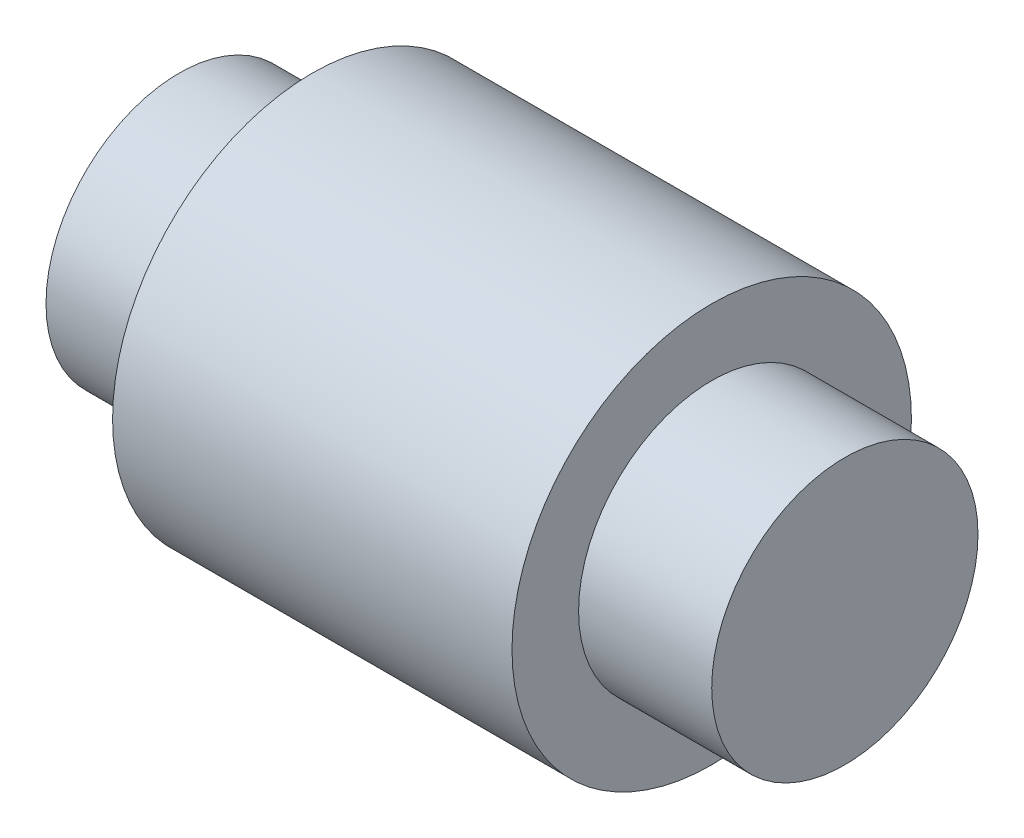
SolidWorks part; units mm, degrees
ref_plane "Спереди" through (0, 0, 0) normal (0, 0, 1) x (1, 0, 0)
ref_plane "Сверху" through (0, 0, 0) normal (0, 1, 0) x (1, 0, 0)
ref_plane "Справа" through (0, 0, 0) normal (1, 0, 0) x (0, 0, -1)
sketch "Эскиз1" plane through (0, 0, 0) normal (0, 0, 1) x (1, 0, 0)
  line L0 (0, 0) -> (100, 0)
  line L1 (0, 0) -> (0, 20)
  line L2 (0, 20) -> (20, 20)
  line L3 (20, 20) -> (20, 30)
  line L4 (20, 30) -> (80, 30)
  line L5 (80, 30) -> (80, 20)
  line L6 (80, 20) -> (100, 20)
  line L7 (100, 20) -> (100, 0)
revolve "Повернуть1" add sketch "Эскиз1" angle 360 about L0
